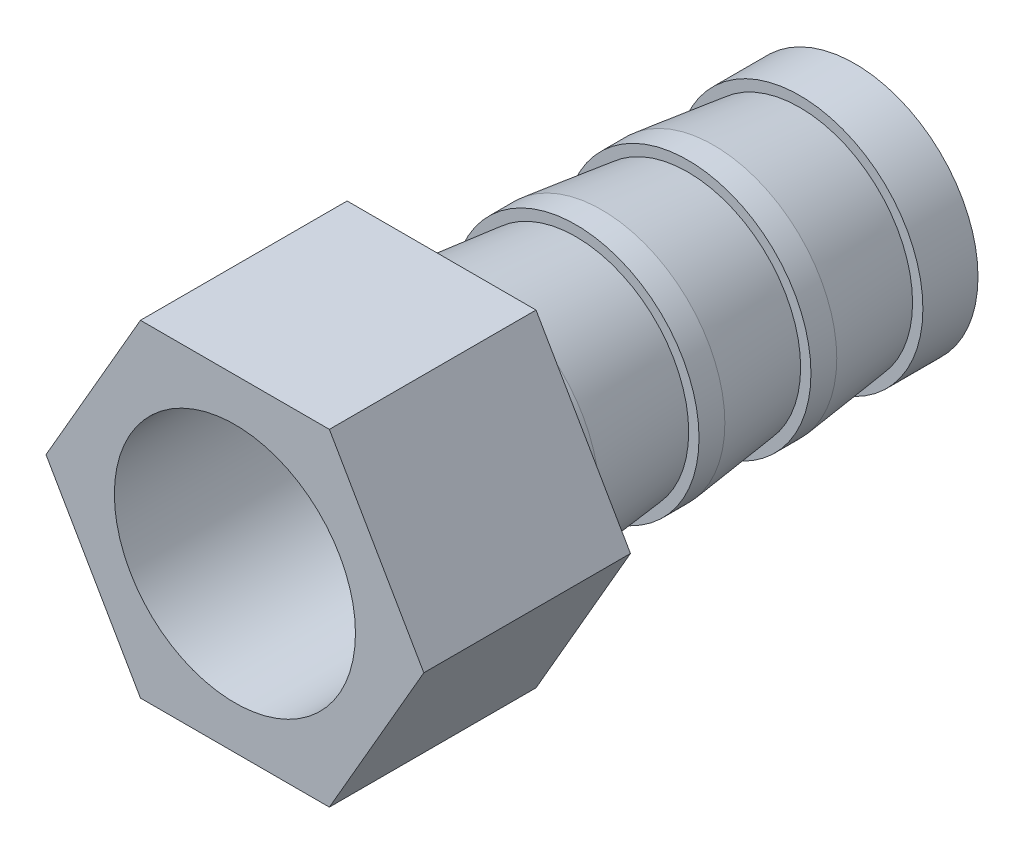
SolidWorks part; units mm, degrees
material "黄铜"
ref_plane "前视基准面" through (0, 0, 0) normal (0, 0, 1) x (1, 0, 0)
ref_plane "上视基准面" through (0, 0, 0) normal (0, 1, 0) x (1, 0, 0)
ref_plane "右视基准面" through (0, 0, 0) normal (1, 0, 0) x (0, 0, -1)
sketch "草图1" plane through (0, 0, 0) normal (0, 0, 1) x (1, 0, 0)
  line L1 (5.4848, 9.5) -> (-5.4848, 9.5)
  line L2 (-5.4848, 9.5) -> (-10.9697, 0)
  line L3 (-10.9697, 0) -> (-5.4848, -9.5)
  line L4 (-5.4848, -9.5) -> (5.4848, -9.5)
  line L5 (5.4848, -9.5) -> (10.9697, 0)
  line L6 (10.9697, 0) -> (5.4848, 9.5)
  circle A0 centre (0, 0) radius 9.5 construction
  circle A1 centre (0, 0) radius 7
  dimension "D2" = 14
  dimension "D1" = 19
extrude "凸台-拉伸1" add sketch "草图1" along normal blind 12
cosmetic thread "装饰螺纹线1" parameters "D2"=16.662
sketch "草图2" plane through (0, 0, 0) normal (0, 1, 0) x (1, 0, 0)
  line L0 (0, 0) -> (0, 24) construction
  line L1 (-7.15, 0) -> (-7.15, 2)
  line L2 (5.4848, 0) -> (-5.4848, 0) construction
  line L3 (-7.15, 2) -> (-6.55, 7.8)
  line L4 (-6.55, 7.8) -> (-7.15, 7.8)
  line L5 (-7.15, 7.8) -> (-7.15, 9.3)
  line L6 (-6.55, 14.3) -> (-7.15, 14.3)
  line L7 (-7.15, 14.3) -> (-7.15, 15.8)
  line L8 (-6.55, 20.8) -> (-7.15, 20.8)
  line L9 (-7.15, 20.8) -> (-7.15, 24)
  line L10 (-7.15, 24) -> (-6, 24)
  line L11 (-6, 24) -> (-6, 0)
  line L12 (-7.15, 9.3) -> (-6.55, 14.3)
  line L13 (-7.15, 15.8) -> (-6.55, 20.8)
  line L14 (-7.15, 0) -> (-6, 0)
  dimension "D1" = 24
  dimension "D2" = 3.2
  dimension "D3" = 12
  dimension "D4" = 14.3
  dimension "D5" = 13.1
  dimension "D6" = 1.5
  dimension "D7" = 6.5
  dimension "D8" = 6.5
  dimension "D9" = 2
revolve "旋转1" add sketch "草图2" angle 360 about L0
sketch3d "URDF Reference"
  line L0 (0, 0, 0) -> (10, 0, 0) construction
  line L1 (0, 0, 0) -> (0, 0, -10) construction
  point P0 (0, 0, 0)
  point P1 (0, 0, 0)
